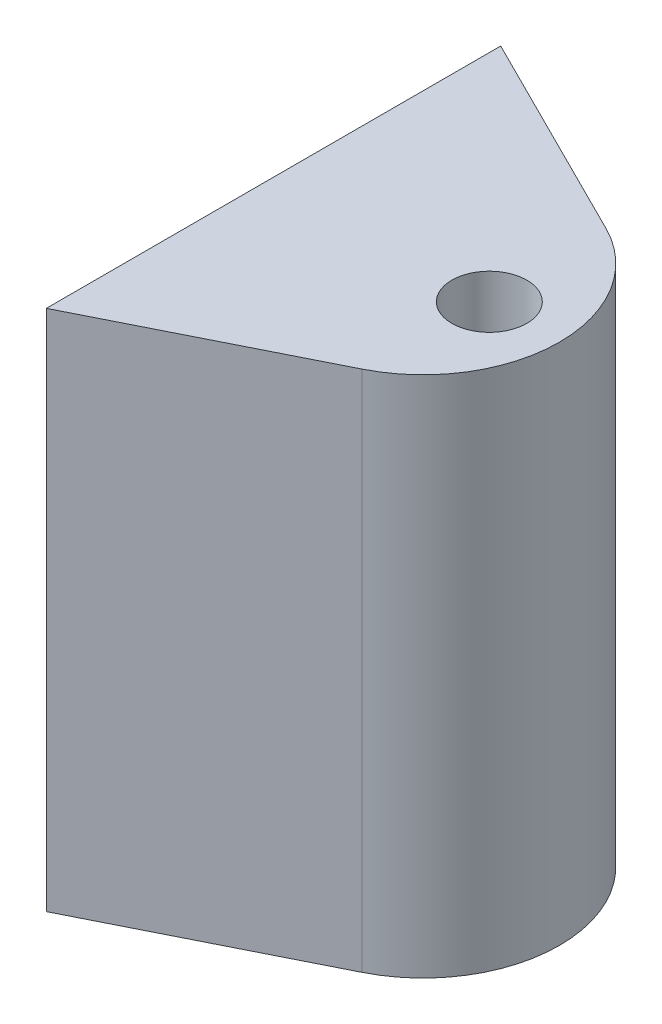
SolidWorks part; units mm, degrees
ref_plane "Front Plane" through (0, 0, 0) normal (0, 0, 1) x (1, 0, 0)
ref_plane "Top Plane" through (0, 0, 0) normal (0, 1, 0) x (1, 0, 0)
ref_plane "Right Plane" through (0, 0, 0) normal (1, 0, 0) x (0, 0, -1)
sketch "Sketch2" plane through (0, 0, 0) normal (1, 0, 0) x (0, 0, -1)
  line L0 (-58.6588, 3.3646) -> (-38.6588, 3.3646)
  line L2 (-48.6588, -16.6354) -> (-38.6588, 3.3646)
  line L3 (-58.6588, 3.3646) -> (-48.6588, -16.6354)
  line L4 (-48.6588, -16.6354) -> (-58.6588, 3.3646)
extrude "Boss-Extrude1" add sketch "Sketch2" along normal blind 23 contours L0 L3 L2
fillet "Fillet1" radius 6 1 edges at (11.5, -16.6354, 48.6588)
sketch3d "3DSketch4"
  line L0 (0, 3.3646, 48.6588) -> (0, -6.1354, 48.6588)
  line L1 (0, 3.3646, 58.6588) -> (0, 3.3646, 38.6588) construction
hole_wizard "Preforo da maschiare M4-1" positions "Sketch4" profile "Sketch5" hole size "M4" standard "GB" end condition through all
sketch "Sketch4" plane through (0, 0, 0) normal (-1, 0, 0) x (0, 0, 1)
  point P0 (48.6588, -6.1354)
sketch "Sketch5" plane through (0, -6.1354, 48.6588) normal (0, 1, 0) x (0, 0, 1)
  line L0 (0, 0) -> (0, 23)
  line L1 (0, 23) -> (1.65, 23)
  line L2 (1.65, 23) -> (1.65, 0)
  line L5 (1.65, 0) -> (0, 0)
  line L11 (0, -6.35) -> (0, 107.95) construction
  dimension "Thru Hole Dia." = 3.3
  dimension "Thru Hole Depth" = 23
move or copy body "Body-Move/Copy1" bodies to move or copy 106 copy no rotation origin (10, -2.9272, 0) rotation axis (0, 0, 1) rotation angle 90
